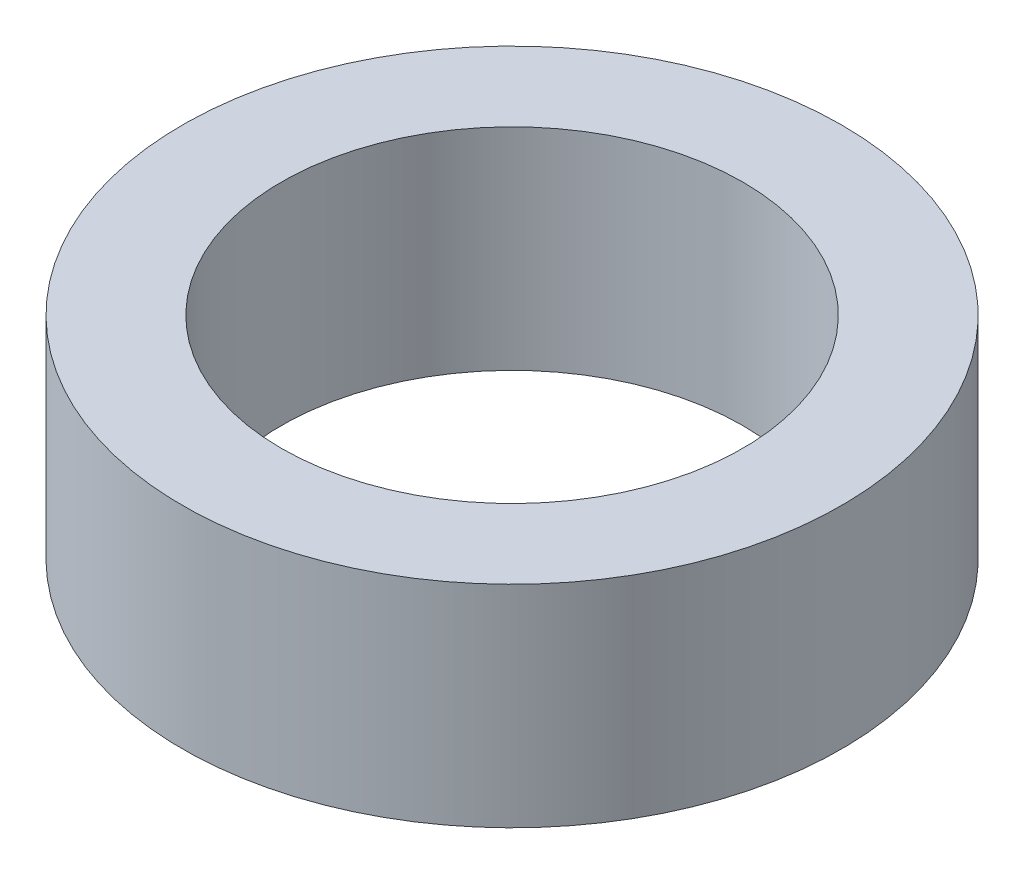
SolidWorks part; units mm, degrees
ref_plane "Front Plane" through (0, 0, 0) normal (0, 0, 1) x (1, 0, 0)
ref_plane "Top Plane" through (0, 0, 0) normal (0, 1, 0) x (1, 0, 0)
ref_plane "Right Plane" through (0, 0, 0) normal (1, 0, 0) x (0, 0, -1)
sketch "Sketch1" plane through (0, 0, 0) normal (0, 0, 1) x (1, 0, 0)
  line L0 (0, 0) -> (0, 45.403) construction
  line L2 (22.225, 0) -> (31.75, 0)
  line L3 (22.225, 0) -> (22.225, 20.32)
  line L4 (22.225, 20.32) -> (31.75, 20.32)
  line L5 (31.75, 0) -> (31.75, 20.32)
  dimension "D1" = 20.32
  dimension "D2" = 44.45
  dimension "D3" = 63.5
revolve "Revolve1" add sketch "Sketch1" angle 360 about L0
